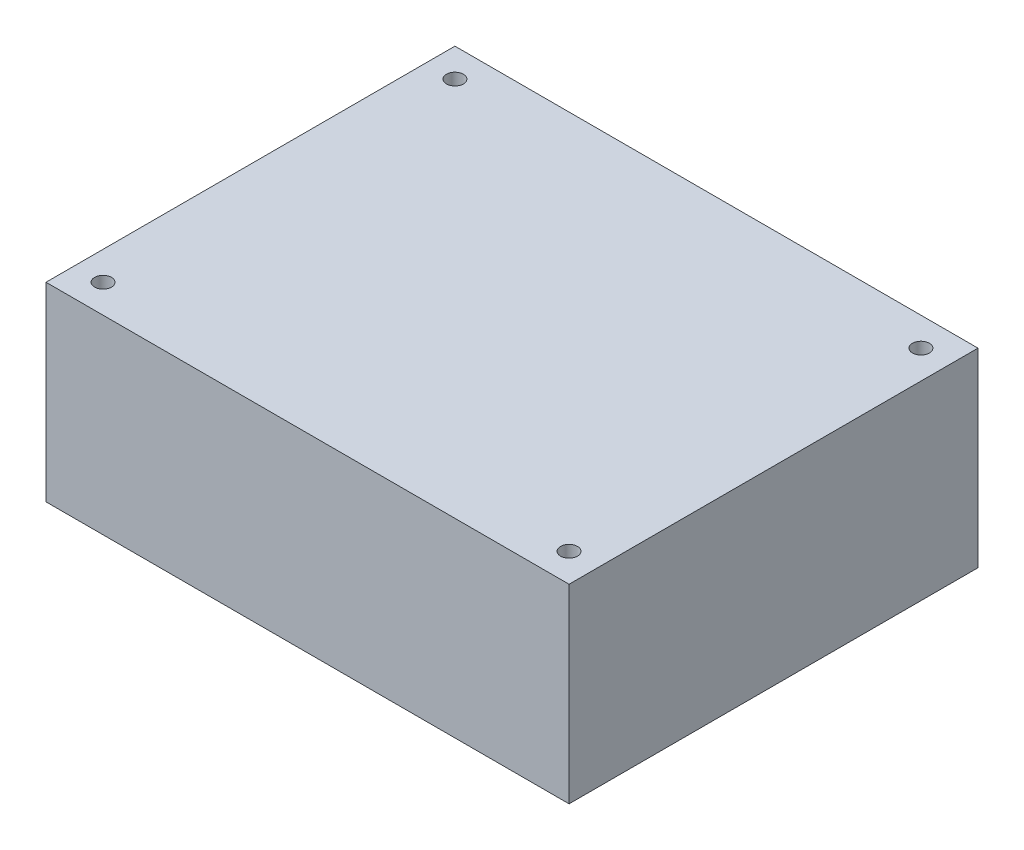
SolidWorks part; units mm, degrees
ref_plane "Front Plane" through (0, 0, 0) normal (0, 0, 1) x (1, 0, 0)
ref_plane "Top Plane" through (0, 0, 0) normal (0, 1, 0) x (1, 0, 0)
ref_plane "Right Plane" through (0, 0, 0) normal (1, 0, 0) x (0, 0, -1)
sketch "Sketch1" plane through (0, 0, 0) normal (0, 1, 0) x (1, 0, 0)
  line L1 (-34.925, 27.305) -> (34.925, 27.305)
  line L2 (-34.925, 27.305) -> (-34.925, -27.305)
  line L3 (-34.925, -27.305) -> (34.925, -27.305)
  line L4 (34.925, 27.305) -> (34.925, -27.305)
  line L5 (-34.925, 27.305) -> (34.925, -27.305) construction
  line L6 (-34.925, -27.305) -> (34.925, 27.305) construction
  point P0 (0, 0)
  dimension "D1" = 54.61
  dimension "D2" = 69.85
extrude "Boss-Extrude1" add sketch "Sketch1" along normal blind 25.4
sketch "Sketch2" plane through (0, 25.4, 0) normal (0, 1, 0) x (1, 0, 0)
  line L0 (0, 0) -> (0, 27.305) construction
  line L1 (34.925, 27.305) -> (-34.925, 27.305) construction
  line L2 (0, 0) -> (-34.925, 0) construction
  line L3 (-34.925, 27.305) -> (-34.925, -27.305) construction
  circle A0 centre (-31.115, 23.495) radius 1.1303
  circle A1 centre (31.115, 23.495) radius 1.1303
  circle A2 centre (31.115, -23.495) radius 1.1303
  circle A3 centre (-31.115, -23.495) radius 1.1303
  dimension "D1" = 2.2606
  dimension "D2" = 3.81
  dimension "D3" = 31.115
  dimension "D4" = 3.81
extrude "Cut-Extrude1" cut sketch "Sketch2" against normal up to surface (25.4 mm away) up to face at (0, 0, 0)
